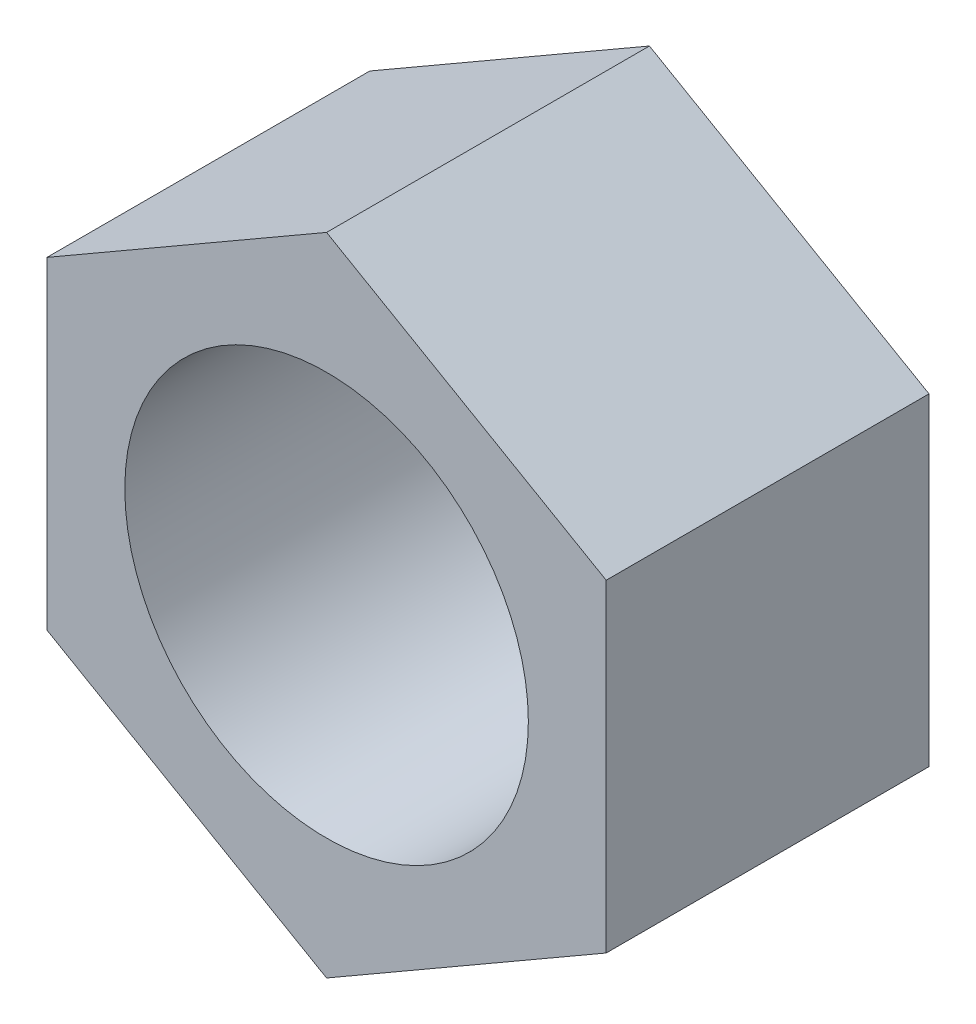
SolidWorks part; units mm, degrees
ref_plane "Front Plane" through (0, 0, 0) normal (0, 0, 1) x (1, 0, 0)
ref_plane "Top Plane" through (0, 0, 0) normal (0, 1, 0) x (1, 0, 0)
ref_plane "Right Plane" through (0, 0, 0) normal (1, 0, 0) x (0, 0, -1)
sketch "Sketch1" plane through (0, 0, 0) normal (0, 0, 1) x (1, 0, 0)
  line L1 (0, -12) -> (10.3923, -6)
  line L2 (10.3923, -6) -> (10.3923, 6)
  line L3 (10.3923, 6) -> (0, 12)
  line L4 (0, 12) -> (-10.3923, 6)
  line L5 (-10.3923, 6) -> (-10.3923, -6)
  line L6 (-10.3923, -6) -> (0, -12)
  circle A0 centre (0, 0) radius 10.3923 construction
  dimension "D1" = 12
extrude "Boss-Extrude1" add sketch "Sketch1" along normal blind 12
sketch "Sketch2" plane through (0, 0, 12) normal (0, 0, 1) x (1, 0, 0)
  circle A0 centre (0, 0) radius 7.5
  dimension "D1" = 15
extrude "Cut-Extrude1" cut sketch "Sketch2" against normal through all both and the other way through all
